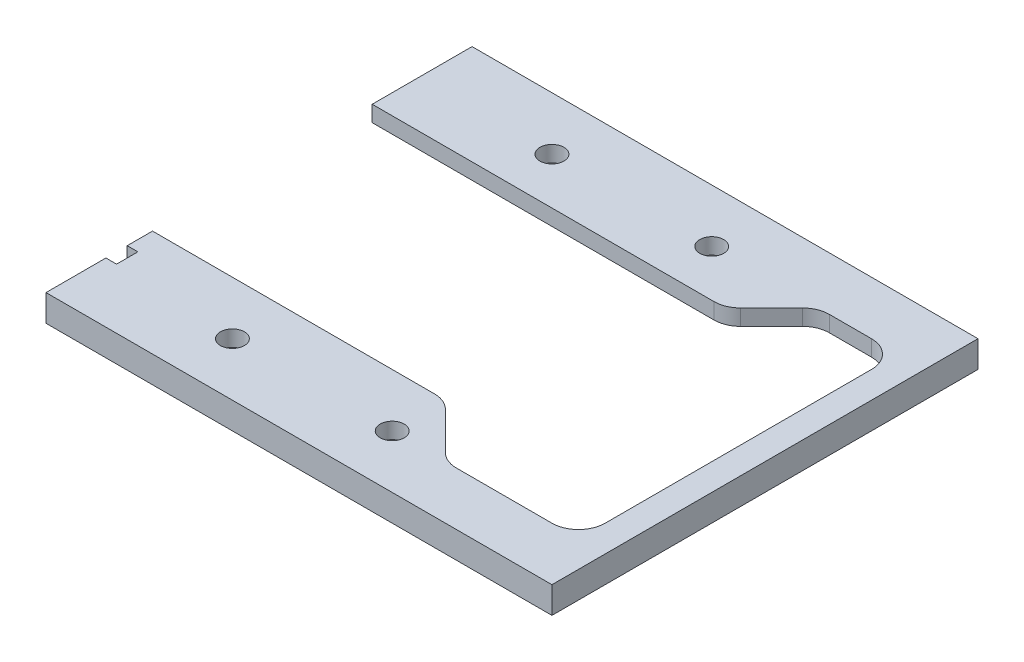
SolidWorks part; units mm, degrees
ref_plane "Front Plane" through (0, 0, 0) normal (0, 0, 1) x (1, 0, 0)
ref_plane "Top Plane" through (0, 0, 0) normal (0, 1, 0) x (1, 0, 0)
ref_plane "Right Plane" through (0, 0, 0) normal (1, 0, 0) x (0, 0, -1)
sketch "Sketch1" plane through (0, 0, 0) normal (0, 1, 0) x (1, 0, 0)
  line L1 (0, 0) -> (190, 0)
  line L2 (0, 0) -> (0, 140)
  line L3 (0, 140) -> (190, 140)
  line L4 (190, 0) -> (190, 140)
  dimension "D1" = 190
  dimension "D2" = 140
extrude "Boss-Extrude1" add sketch "Sketch1" along normal blind 6
sketch "Sketch2" plane through (0, 6, 0) normal (0, 1, 0) x (1, 0, 0)
  line L4 (112.9289, 92.9289) -> (147.0711, 127.0711)
  line L5 (154.1421, 130) -> (170, 130)
  line L6 (180, 120) -> (180, 20)
  line L12 (86.8495, 65.4289) -> (95.5064, 74.0858)
  line L13 (190, 0) -> (190, 140) construction
  line L14 (190, 140) -> (0, 140) construction
  line L15 (105.8579, 90) -> (0, 90)
  line L16 (0, 140) -> (0, 0) construction
  line L17 (94.0922, 77.5) -> (0, 77.5)
  line L18 (190, 140) -> (0, 140) construction
  line L19 (0, 0) -> (190, 0) construction
  line L20 (170, 10) -> (134.1421, 10)
  line L21 (127.0711, 12.9289) -> (95.4289, 44.5711)
  line L22 (88.3579, 47.5) -> (0, 47.5)
  line L39 (0, 62.5) -> (30.447, 62.5)
  line L40 (30.447, 62.5) -> (79.7785, 62.5)
  arc A10 (170, 130) -> (180, 120) centre (170, 120) cw
  arc A11 (180, 20) -> (170, 10) centre (170, 20) cw
  arc A22 (112.9289, 92.9289) -> (105.8579, 90) centre (105.8579, 100) cw
  arc A23 (147.0711, 127.0711) -> (154.1421, 130) centre (154.1421, 120) cw
  arc A24 (88.3579, 47.5) -> (95.4289, 44.5711) centre (88.3579, 37.5) cw
  arc A25 (127.0711, 12.9289) -> (134.1421, 10) centre (134.1421, 20) ccw
  arc A26 (95.5064, 74.0858) -> (94.0922, 77.5) centre (94.0922, 75.5) ccw
  arc A27 (86.8495, 65.4289) -> (79.7785, 62.5) centre (79.7785, 72.5) cw
  point P55 (180, 130)
  point P70 (110, 90)
  point P73 (150, 130)
  point P76 (92.5, 47.5)
  point P79 (130, 10)
  point P82 (98.9206, 77.5)
  point P85 (83.9206, 62.5)
  dimension "D1" = 10
  dimension "D4" = 10
  dimension "D42" = 10
  dimension "D43" = 2
  dimension "D44" = 10
  dimension "D2" = 10
  dimension "D3" = 10
  dimension "D5" = 50
  dimension "D6" = 30
  dimension "D7" = 135
  dimension "D8" = 110
  dimension "D9" = 98.9206
  dimension "D10" = 21.2132
  dimension "D11" = 12.5
  dimension "D12" = 15
  dimension "D13" = 135
  dimension "D14" = 135
  dimension "D15" = 92.5
  dimension "D16" = 40
  dimension "D17" = 10
  dimension "D18" = 50
  dimension "D19" = 47.5
extrude "Cut-Extrude1" cut sketch "Sketch2" against normal blind 10
sketch "Sketch3" plane through (0, 6, 0) normal (0, 1, 0) x (1, 0, 0)
  line L0 (0, 0) -> (190, 0) construction
  line L1 (0, 112.5) -> (150, 112.5)
  line L2 (0, 112.5) -> (0, 30)
  line L3 (0, 30) -> (150, 30)
  line L4 (150, 112.5) -> (150, 30)
  line L5 (190, 140) -> (0, 140) construction
  dimension "D1" = 30
  dimension "D2" = 150
  dimension "D3" = 27.5
sketch "Sketch4" plane through (0, 0, 0) normal (0, -1, 0) x (1, 0, 0)
  line L0 (0, 0) -> (0, 6.1558)
  line L1 (190, 0) -> (190, 10)
  line L2 (190, 10) -> (0, 10)
  line L3 (0, 10) -> (0, 0)
  line L4 (190, 0) -> (0, 0)
  line L5 (190, -140) -> (0, -140) construction
  line L6 (190, 0) -> (185, 0)
  line L7 (190, 0) -> (190, -140)
  line L8 (190, -140) -> (185, -140)
  line L9 (185, 0) -> (185, -140)
  line L11 (0, -140) -> (190, -140)
  line L12 (0, -140) -> (0, -150)
  line L13 (0, -150) -> (190, -150)
  line L14 (190, -140) -> (190, -150)
  line M18 (0, -140) -> (190, -140)
  line M19 (190, -140) -> (190, 0)
  line M20 (190, 0) -> (0, 0)
  dimension "D1" = 10
  dimension "D2" = 10
  dimension "D3" = 5
extrude "Boss-Extrude4" add sketch "Sketch4" along normal blind 4 contours L9 M20 M18 M19
sketch "Sketch5" plane through (190, 0, 0) normal (1, 0, 0) x (0, 0, -1)
  line L1 (140, -4) -> (0, -4)
  line L2 (140, -4) -> (140, 6)
  line L3 (140, 6) -> (0, 6)
  line L4 (0, -4) -> (0, 6)
sketch "Sketch8" plane through (0, 0, 0) normal (0, 0, 1) x (1, 0, 0)
  line L1 (0, 6) -> (190, 6)
  line L2 (0, 6) -> (0, -4)
  line L3 (0, -4) -> (190, -4)
  line L4 (190, 6) -> (190, -4)
extrude "Boss-Extrude8" add sketch "Sketch8" along normal blind 10
sketch "Sketch9" plane through (0, 0, -140) normal (0, 0, -1) x (-1, 0, 0)
  line L1 (0, 6) -> (-190, 6)
  line L2 (0, 6) -> (0, -4)
  line L3 (0, -4) -> (-190, -4)
  line L4 (-190, 6) -> (-190, -4)
extrude "Boss-Extrude9" add sketch "Sketch9" along normal blind 10
sketch "Sketch10" plane through (0, 0, 0) normal (0, -1, 0) x (1, 0, 0)
  line L0 (0, -47.5) -> (0, 0) construction
  line L1 (0, -20.5) -> (4, -20.5)
  line L2 (0, -20.5) -> (0, -12.5)
  line L3 (0, -12.5) -> (4, -12.5)
  line L4 (4, -20.5) -> (4, -12.5)
  line L5 (0, 0) -> (185, 0) construction
  dimension "D1" = 8
  dimension "D2" = 4
  dimension "D3" = 12.5
extrude "Cut-Extrude3" cut sketch "Sketch10" against normal blind 10
sketch "Sketch11" plane through (0, 6, 0) normal (0, 1, 0) x (1, 0, 0)
  line L0 (190, 70) -> (-24.2561, 70) construction
  line L1 (190, -10) -> (190, 150) construction
  line L2 (190, -10) -> (0, -10) construction
  line L3 (190, 150) -> (190, -10) construction
  circle A0 centre (50, 10) radius 3
  circle A1 centre (110, 10) radius 3
  circle A3 centre (110, 130) radius 3
  circle A4 centre (50, 130) radius 3
  dimension "D1" = 6
  dimension "D2" = 6
  dimension "D3" = 20
  dimension "D4" = 20
  dimension "D5" = 80
  dimension "D6" = 140
extrude "Cut-Extrude4" cut sketch "Sketch11" against normal blind 10
sketch "Sketch12" plane through (0, 0, 0) normal (0, 1, 0) x (1, 0, 0)
  line L0 (170, 70) -> (-24.2561, 70) construction
  line L1 (190, -10) -> (190, 150) construction
  circle A0 centre (50, 10) radius 4.5
  circle A1 centre (110, 10) radius 4.5
  circle A3 centre (110, 130) radius 4.5
  circle A4 centre (50, 130) radius 4.5
  dimension "D1" = 9
  dimension "D2" = 9
  dimension "D3" = 140
  dimension "D4" = 80
extrude "Cut-Extrude6" cut sketch "Sketch12" along normal through all
extrude "Cut-Extrude7" cut sketch "Sketch3" against normal blind 10
sketch "Sketch14" plane through (0, 6, 0) normal (0, 1, 0) x (1, 0, 0)
  line L0 (127.0711, 12.9289) -> (112.9289, 27.0711)
  line L1 (105.8579, 30) -> (0, 30)
  line L2 (0, 30) -> (0, 112.5)
  line L3 (0, 112.5) -> (128.3579, 112.5)
  line L4 (135.4289, 115.4289) -> (147.0711, 127.0711)
  line L5 (127.0711, 12.9289) -> (147.0711, 92.6617)
  line L6 (147.0711, 92.6617) -> (147.0711, 127.0711)
  arc A0 (105.8579, 30) -> (112.9289, 27.0711) centre (105.8579, 20) cw
  arc A1 (128.3579, 112.5) -> (135.4289, 115.4289) centre (128.3579, 122.5) ccw
  point P14 (110, 30)
  point P17 (132.5, 112.5)
  dimension "D1" = 10
extrude "Cut-Extrude9" cut sketch "Sketch14" against normal blind 10
